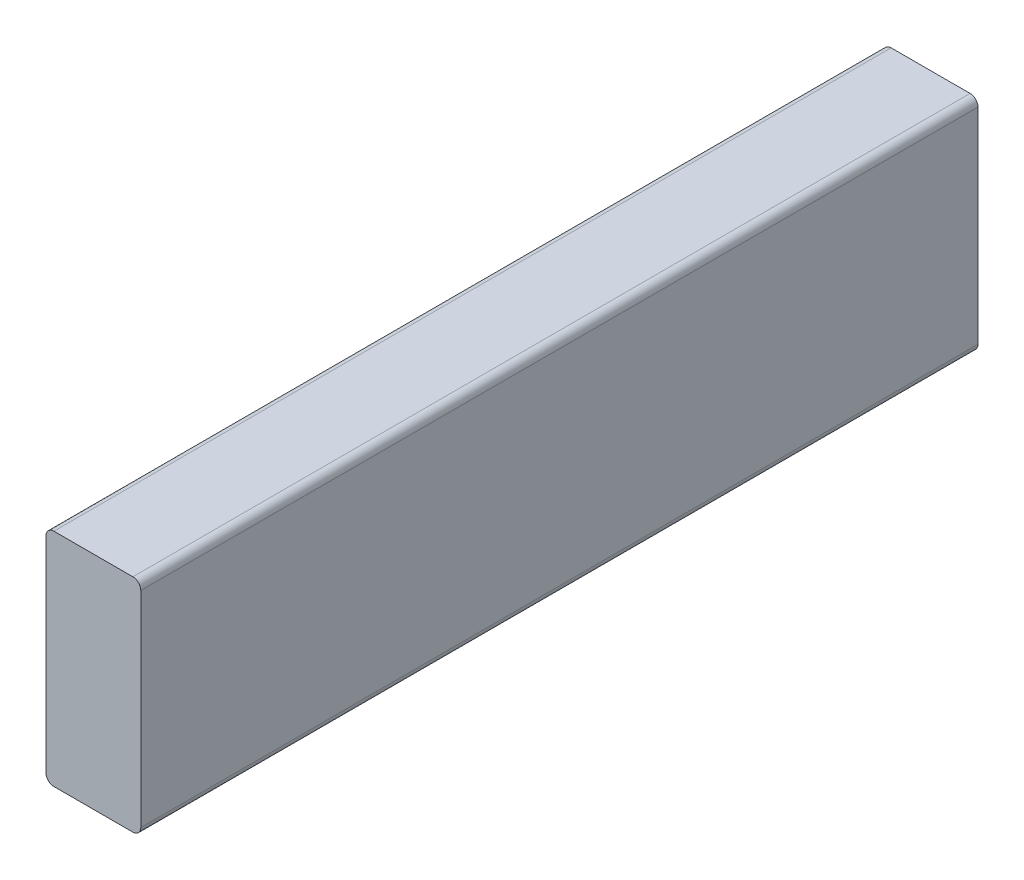
SolidWorks part; units mm, degrees
material "Pine"
ref_plane "Front Plane" through (0, 0, 0) normal (0, 0, 1) x (1, 0, 0)
ref_plane "Top Plane" through (0, 0, 0) normal (0, 1, 0) x (1, 0, 0)
ref_plane "Right Plane" through (0, 0, 0) normal (1, 0, 0) x (0, 0, -1)
sketch "Sketch1" plane through (0, 0, 0) normal (0, 0, 1) x (1, 0, 0)
  line L1 (-19.05, 44.45) -> (19.05, 44.45)
  line L2 (-19.05, 44.45) -> (-19.05, -44.45)
  line L3 (-19.05, -44.45) -> (19.05, -44.45)
  line L4 (19.05, 44.45) -> (19.05, -44.45)
  line L5 (-19.05, 44.45) -> (19.05, -44.45) construction
  line L6 (-19.05, -44.45) -> (19.05, 44.45) construction
  point P0 (0, 0)
  dimension "D1" = 38.1
  dimension "D2" = 88.9
extrude "Boss-Extrude1" add sketch "Sketch1" against normal blind 336.55
fillet "Fillet1" radius 3.175 4 edges at (-19.05, 44.45, -168.275) (-19.05, -44.45, -168.275) (19.05, -44.45, -168.275) (19.05, 44.45, -168.275)
